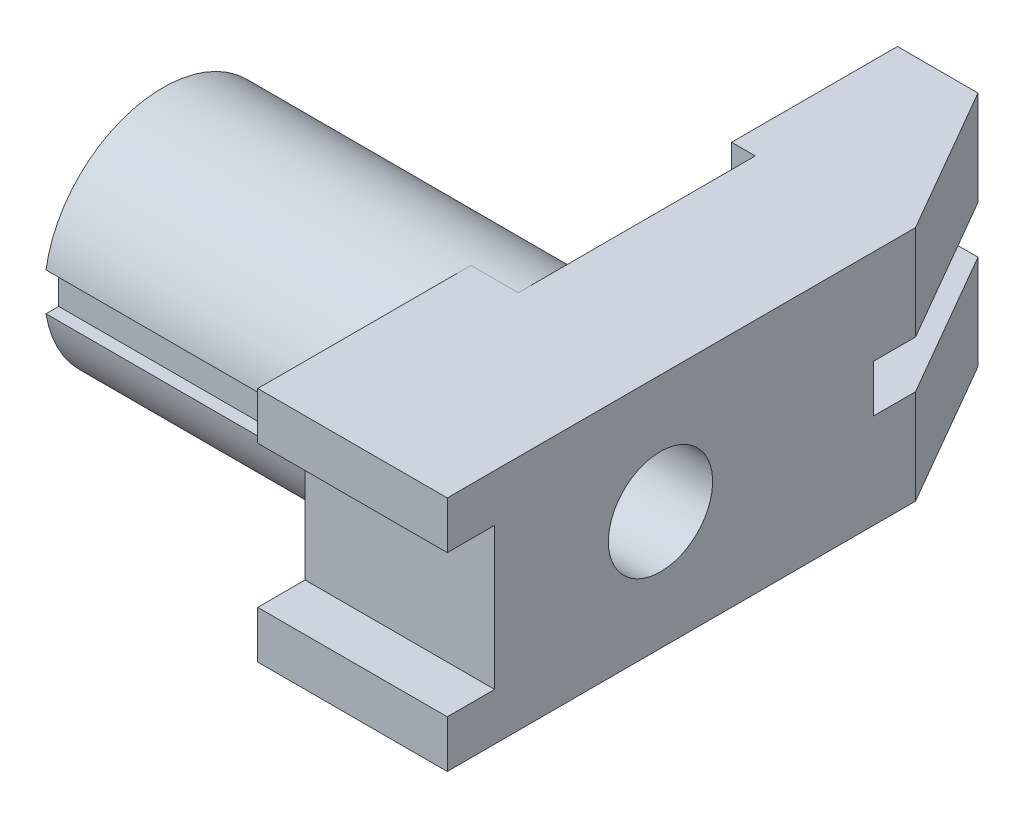
SolidWorks part; units mm, degrees
ref_plane "Спереди" through (0, 0, 0) normal (0, 0, 1) x (1, 0, 0)
ref_plane "Сверху" through (0, 0, 0) normal (0, 1, 0) x (1, 0, 0)
ref_plane "Справа" through (0, 0, 0) normal (1, 0, 0) x (0, 0, -1)
sketch "Эскиз1" plane through (0, 0, 0) normal (0, 1, 0) x (1, 0, 0)
  line L0 (-994.9506, 0) -> (48752.5781, 0) construction
  line L1 (0, -987.331) -> (0, 48760.1976) construction
  line L2 (0, 0) -> (0, 98.8231)
  line L3 (0, 98.8231) -> (-18, 130)
  line L4 (-18, 130) -> (-35, 130)
  line L5 (-35, 130) -> (-35, 95)
  line L6 (-35, 95) -> (-30, 95)
  line L7 (-30, 95) -> (-30, 89.5245)
  line L8 (-30, 89.5245) -> (-30, 70)
  line L9 (-30, 70) -> (-105, 70)
  line L10 (-105, 70) -> (-105, 20)
  line L11 (-105, 20) -> (-40, 20)
  line L12 (-40, 20) -> (-40, 0)
  line L13 (-40, 0) -> (0, 0)
  dimension "D1" = 17
  dimension "D2" = 130
  dimension "D3" = 30
  dimension "D4" = 35
  dimension "D5" = 5
  dimension "D6" = 70
  dimension "D7" = 95
  dimension "D8" = 50
  dimension "D9" = 105
  dimension "D10" = 40
extrude "Бобышка-Вытянуть1" add sketch "Эскиз1" along normal mid plane 50
sketch "Эскиз3" plane through (0, 0, 0) normal (1, 0, 0) x (0, 0, -1)
  line L0 (-1000, 0) -> (49000, 0) construction
  line L1 (0, 25) -> (0, -25) construction
  line L2 (90, 5) -> (130, 5)
  line L3 (90, 5) -> (90, -5)
  line L4 (90, -5) -> (130, -5)
  line L5 (130, 5) -> (130, -5)
  line L6 (90, 5) -> (130, -5) construction
  line L7 (90, -5) -> (130, 5) construction
  line L9 (10, 15) -> (0, 15)
  line L10 (10, 15) -> (10, -15)
  line L11 (10, -15) -> (0, -15)
  line L12 (0, 15) -> (0, -15)
  line L13 (10, 15) -> (0, -15) construction
  line L14 (10, -15) -> (0, 15) construction
  point P1 (110, 0)
  point P10 (5, 0)
  dimension "D1" = 90
  dimension "D2" = 130
  dimension "D3" = 10
  dimension "D4" = 10
  dimension "D5" = 30
extrude "Вырез-Вытянуть1" cut sketch "Эскиз3" against normal up to next
sketch "Эскиз4" plane through (-105, 0, 0) normal (-1, 0, 0) x (0, 0, 1)
  line L0 (0, 25) -> (0, 15) construction
  line L1 (-70, 25) -> (-20, 25) construction
  line L3 (-20, -25) -> (-70, -25)
  line L4 (-20, -25) -> (-20, 25)
  line L5 (-20, 25) -> (-70, 25)
  line L6 (-70, -25) -> (-70, 25)
  line L7 (-20, -25) -> (-70, 25) construction
  line L8 (-20, 25) -> (-70, -25) construction
  circle A0 centre (-45, 0) radius 25
  line M2 (-70, -25) -> (-20, -25)
  line M5 (-70, 25) -> (-70, -25)
  dimension "D2" = 50
  dimension "D1" = 45
extrude "Вырез-Вытянуть2" cut sketch "Эскиз4" against normal blind 75 contours A0 L6 M2 | A0 L5 M5
sketch "Эскиз6" plane through (-105, 0, 0) normal (-1, 0, 0) x (0, 0, 1)
  line L0 (-20, 25) -> (-20, -25) construction
  line L2 (-70, -25) -> (-20, -25)
  line L3 (-70, -25) -> (-70, 25)
  line L4 (-70, 25) -> (-20, 25)
  line L5 (-20, -25) -> (-20, 25)
  line L6 (-70, -25) -> (-20, 25) construction
  line L7 (-70, 25) -> (-20, -25) construction
  circle A0 centre (-45, 0) radius 25
  line M1 (-20, 25) -> (-45, 25)
  line M3 (-45, -25) -> (-20, -25)
  line M4 (-20, -25) -> (-20, 25)
extrude "Вырез-Вытянуть3" cut sketch "Эскиз6" against normal blind 65 contours A0 M3 M4 | A0 L5 M1
sketch "Эскиз7" plane through (0, 0, 0) normal (0, 1, 0) x (1, 0, 0)
  line L0 (-105, 20) -> (-105, 23)
  line L1 (-105, 23) -> (-55, 23)
  line L2 (-55, 23) -> (-55, 20)
  line L3 (-105, 20) -> (-40, 20) construction
  line L4 (-55, 20) -> (-105, 20)
  line L5 (-55, 20) -> (-47.8586, 20)
  circle A0 centre (-55, 13) radius 10
  dimension "D1" = 20
  dimension "D2" = 3
  dimension "D3" = 50
extrude "Вырез-Вытянуть4" cut sketch "Эскиз7" against normal mid plane 8 contours A0 L1 L0 L4 | L2 A0 L4 | L5 A0 L2
sketch "Эскиз8" plane through (-105, 0, 0) normal (-1, 0, 0) x (0, 0, 1)
  circle A0 centre (-45, 0) radius 18
  arc A1 (-20.3221, 4) -> (-20.3221, -4) centre (-45, 0) ccw construction
  dimension "D1" = 36
extrude "Вырез-Вытянуть5" cut sketch "Эскиз8" against normal blind 53
sketch "Эскиз9" plane through (-52, 0, 0) normal (-1, 0, 0) x (0, 0, 1)
  circle A0 centre (-45, 0) radius 11
  circle A1 centre (-45, 0) radius 18 construction
  dimension "D1" = 22
extrude "Вырез-Вытянуть6" cut sketch "Эскиз9" against normal up to next
